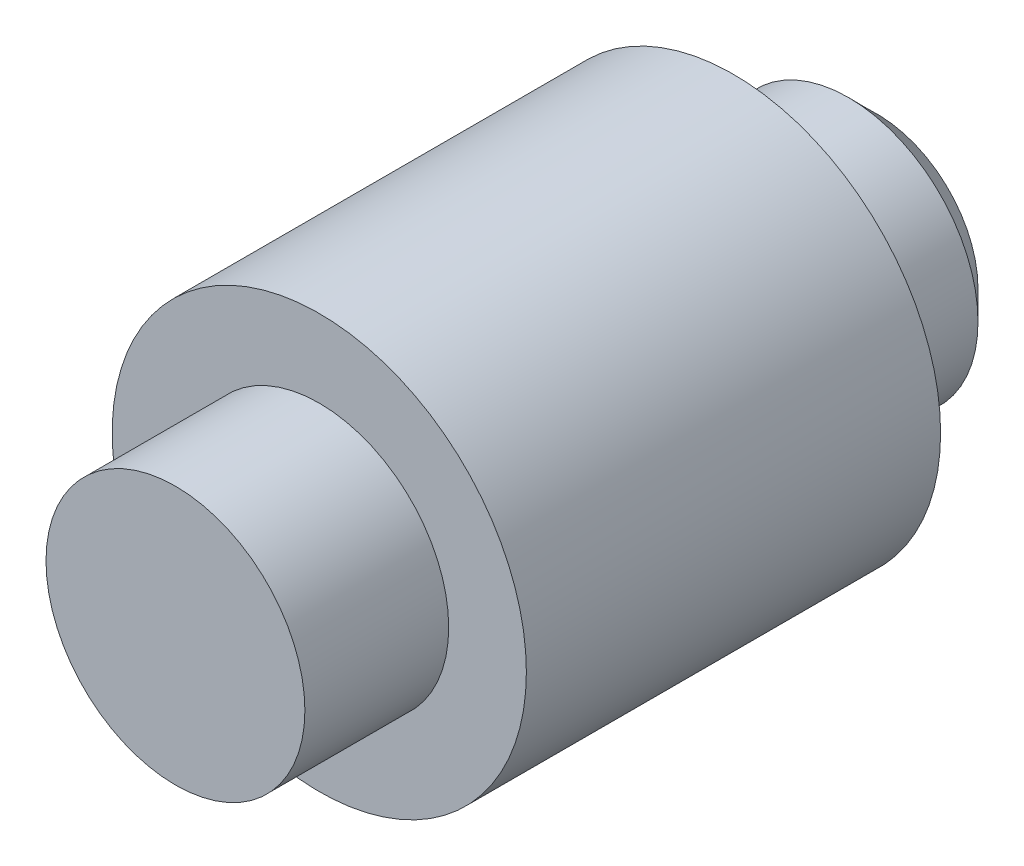
SolidWorks part; units mm, degrees
ref_plane "Front Plane" through (0, 0, 0) normal (0, 0, 1) x (1, 0, 0)
ref_plane "Top Plane" through (0, 0, 0) normal (0, 1, 0) x (1, 0, 0)
ref_plane "Right Plane" through (0, 0, 0) normal (1, 0, 0) x (0, 0, -1)
sketch "Sketch2" plane through (0, 0, 0) normal (0, 0, 1) x (1, 0, 0)
  circle A0 centre (0, 0) radius 1.25
  dimension "D1" = 2.5
sketch "Sketch3" plane through (0, 0, 0) normal (0, 0, 1) x (1, 0, 0)
  line L5 (-3.6, 3.6) -> (3.6, 3.6) construction
  line L6 (-3.6, 3.6) -> (-3.6, -3.6) construction
  line L7 (-3.6, -3.6) -> (3.6, -3.6) construction
  line L8 (3.6, 3.6) -> (3.6, -3.6) construction
  circle A0 centre (0, 0) radius 3.6
  point P4 (0, 3.6)
  point P6 (-3.6, 0)
  dimension "D1" = 7.2
extrude "Boss-Extrude1" add sketch "Sketch3" along normal blind 7.2
sketch "Sketch4" plane through (0, 0, 0) normal (0, 0, 1) x (1, 0, 0)
  circle A0 centre (0, 0) radius 2.25
  dimension "D1" = 4.5
extrude "Boss-Extrude2" add sketch "Sketch4" against normal blind 2.5
sketch "Sketch5" plane through (0, 0, 7.2) normal (0, 0, 1) x (1, 0, 0)
  circle A0 centre (0, 0) radius 2.25
  dimension "D1" = 4.5
extrude "Boss-Extrude3" add sketch "Sketch5" along normal blind 2.5
chamfer "Chamfer1" distance 0.5 angle 45 1 edges at (2.25, 0, -2.5)
equation "\"length\"=7.2"
equation "\"D1@Boss-Extrude1\"=\"length\""
equation "\"hole\"=4.5"
equation "\"D1@Sketch5\"=\"hole\""
equation "\"D1@Sketch4\"=\"hole\""
